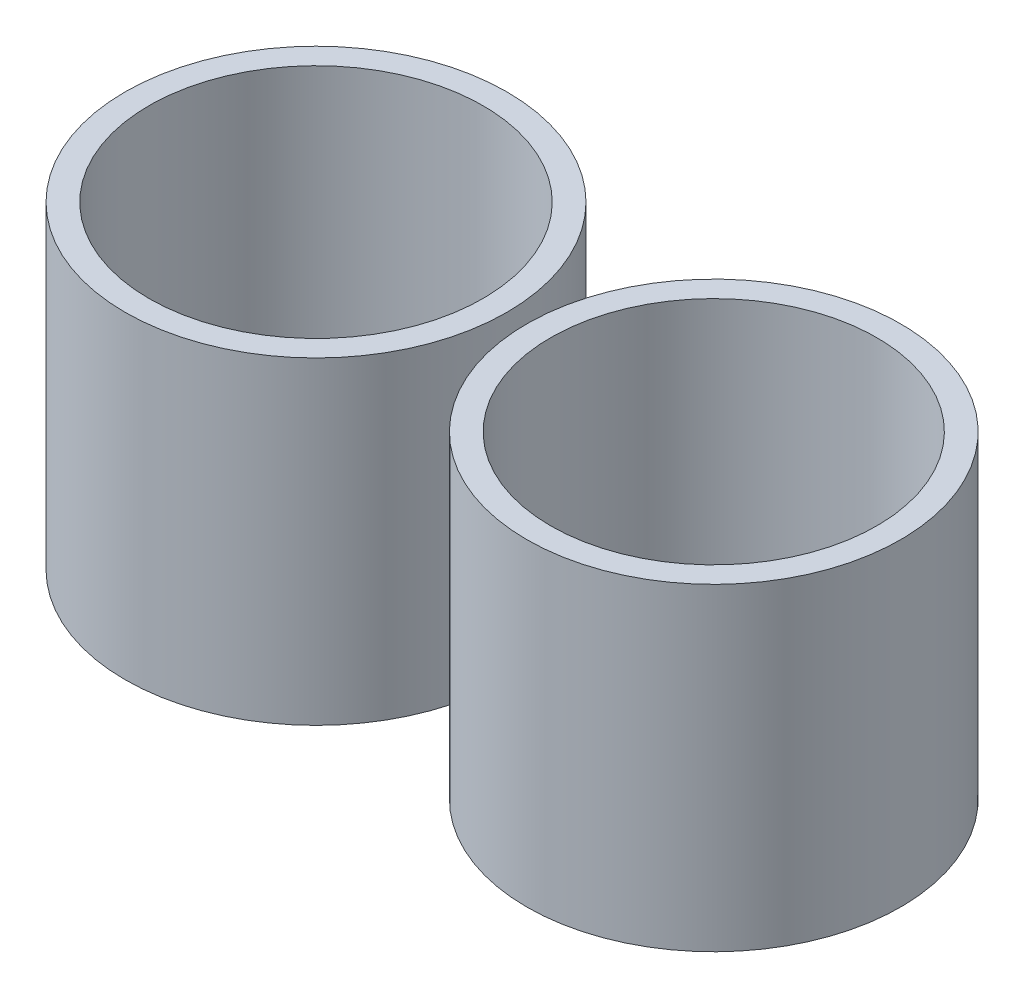
SolidWorks part; units mm, degrees
ref_plane "Front Plane" through (0, 0, 0) normal (0, 0, 1) x (1, 0, 0)
ref_plane "Top Plane" through (0, 0, 0) normal (0, 1, 0) x (1, 0, 0)
ref_plane "Right Plane" through (0, 0, 0) normal (1, 0, 0) x (0, 0, -1)
sketch "Sketch2" plane through (0, 0, 0) normal (0, 1, 0) x (1, 0, 0)
  circle A0 centre (0, 0) radius 11.75
  dimension "D1" = 23.5
extrude "Boss-Extrude1" add sketch "Sketch2" along normal blind 20
sketch "Sketch3" plane through (0, 20, 0) normal (0, 1, 0) x (1, 0, 0)
  circle A0 centre (0, 0) radius 10.25
  circle A1 centre (0, 0) radius 11.75 construction
  dimension "D1" = 1.5
extrude "Cut-Extrude1" cut sketch "Sketch3" against normal through all both and the other way through all
sketch "Sketch4" plane through (0, 0, 0) normal (0, 1, 0) x (1, 0, 0)
  circle A0 centre (-25, 0) radius 12
  dimension "D1" = 24
  dimension "D2" = 25
extrude "Boss-Extrude2" add sketch "Sketch4" along normal blind 20 separate body
sketch "Sketch5" plane through (0, 20, 0) normal (0, 1, 0) x (1, 0, 0)
  circle A0 centre (-25, 0) radius 10.5
  dimension "D1" = 21
extrude "Cut-Extrude2" cut sketch "Sketch5" against normal through all both and the other way through all
